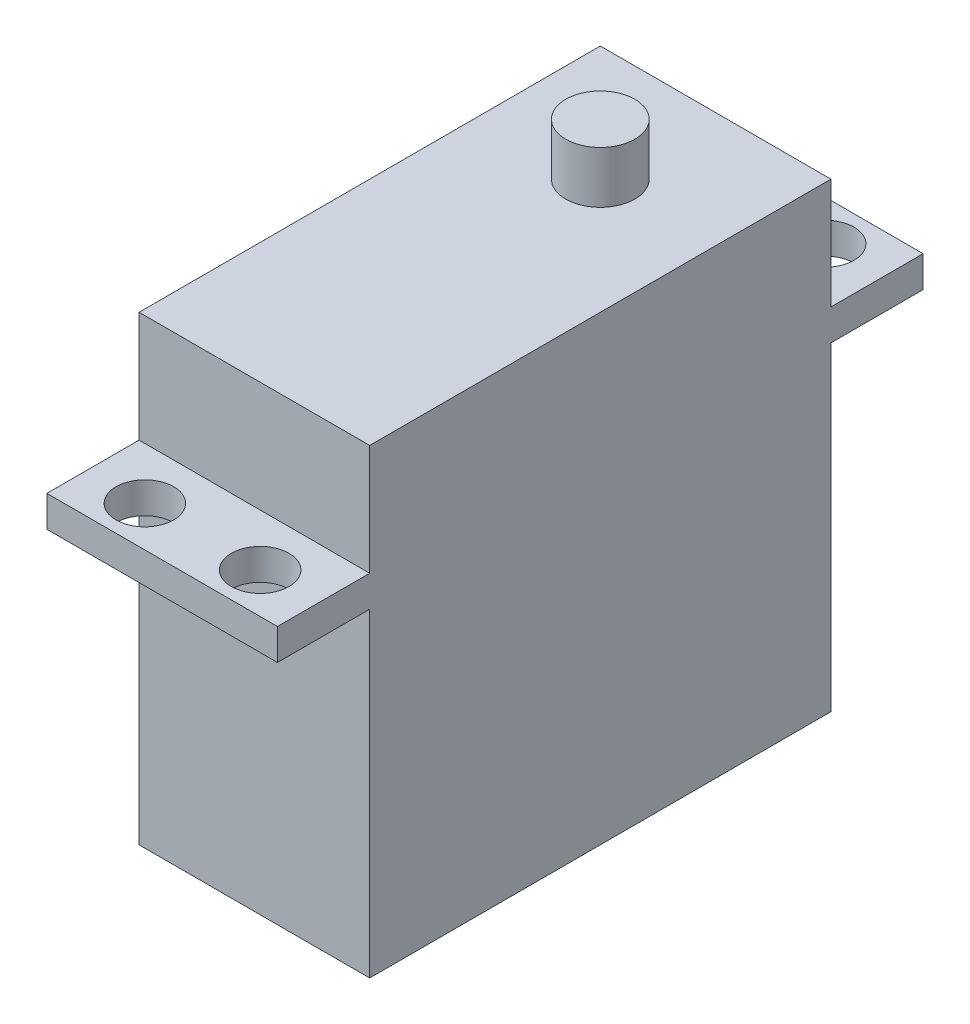
SolidWorks part; units mm, degrees
ref_plane "前基準面" through (0, 0, 0) normal (0, 0, 1) x (1, 0, 0)
ref_plane "上基準面" through (0, 0, 0) normal (0, 1, 0) x (1, 0, 0)
ref_plane "右基準面" through (0, 0, 0) normal (1, 0, 0) x (0, 0, -1)
sketch "草圖1" plane through (0, 0, 0) normal (0, 1, 0) x (1, 0, 0)
  line L1 (-10, 20) -> (10, 20)
  line L2 (-10, 20) -> (-10, -20)
  line L3 (-10, -20) -> (10, -20)
  line L4 (10, 20) -> (10, -20)
  line L5 (-10, 20) -> (10, -20) construction
  line L6 (-10, -20) -> (10, 20) construction
  point P0 (0, 0)
  dimension "D1" = 20
  dimension "D2" = 40
extrude "填料-伸長1" add sketch "草圖1" along normal blind 40
sketch "草圖3" plane through (10, 0, 0) normal (1, 0, 0) x (0, 0, -1)
  line L0 (20, 40) -> (20, 0) construction
  line L1 (20, 30.4) -> (28, 30.4)
  line L2 (20, 30.4) -> (20, 27.7)
  line L3 (20, 27.7) -> (28, 27.7)
  line L4 (28, 30.4) -> (28, 27.7)
  line L5 (-20, 40) -> (-20, 0) construction
  line L6 (-20, 30.4) -> (-28, 30.4)
  line L7 (-20, 30.4) -> (-20, 27.7)
  line L8 (-20, 27.7) -> (-28, 27.7)
  line L9 (-28, 30.4) -> (-28, 27.7)
  line L10 (-20, 0) -> (20, 0) construction
  dimension "D1" = 2.7
  dimension "D2" = 27.7
  dimension "D3" = 8
  dimension "D4" = 2.7
  dimension "D5" = 8
  dimension "D6" = 27.7
extrude "填料-伸長2" add sketch "草圖3" against normal up to surface (20 mm away) up to face at (-10, 20, 0)
sketch "草圖4" plane through (0, 30.4, 0) normal (0, 1, 0) x (1, 0, 0)
  line L0 (-10, 20) -> (10, 20) construction
  line L1 (10, 20) -> (-10, 20) construction
  line L3 (-5, 24.5) -> (5, 24.5) construction
  line L4 (-55, 0) -> (55, 0) construction
  line L5 (-5, -24.5) -> (5, -24.5) construction
  circle A0 centre (5, 24.5) radius 2.5
  circle A1 centre (-5, 24.5) radius 2.5
  circle A2 centre (-5, -24.5) radius 2.5
  circle A3 centre (5, -24.5) radius 2.5
  point P8 (0, 24.5)
  dimension "D3" = 5
  dimension "D5" = 5
  dimension "D1" = 4.5
  dimension "D2" = 4.5
  dimension "D4" = 10
extrude "除料-伸長1" cut sketch "草圖4" against normal blind 40
sketch "草圖5" plane through (0, 40, 0) normal (0, 1, 0) x (1, 0, 0)
  line L0 (-10, 20) -> (10, 20) construction
  circle A0 centre (0, 10) radius 3
  point P4 (0, 0)
  point P5 (0, 0)
  dimension "D2" = 6
  dimension "D1" = 10
extrude "填料-伸長3" add sketch "草圖5" along normal blind 4.5
